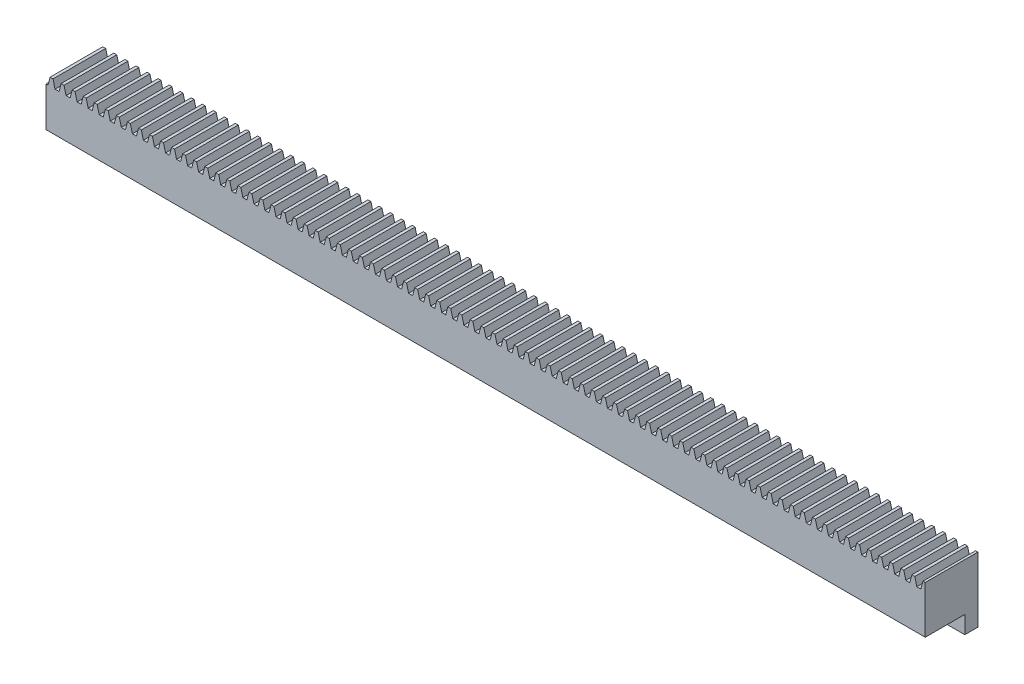
SolidWorks part; units mm, degrees
extrude "Blank" add sketch "BlankSke" against normal blind 12
sketch "BlankSke" plane through (0, 0, 0) normal (0, 0, 1) x (1, 0, 0)
  line L1 (0, 0) -> (200, 0)
  line L2 (0, 0) -> (0, 10.8)
  line L3 (0, 10.8) -> (200, 10.8)
  line L4 (200, 0) -> (200, 10.8)
  dimension "Length" = 200
  dimension "Blank_height" = 10.8
ref_plane "Plane1" through (0, 0, 0) normal (0, 0, 1) x (1, 0, 0)
ref_plane "Plane2" through (0, 0, 0) normal (0, 1, 0) x (1, 0, 0)
ref_plane "Plane3" through (0, 0, 0) normal (1, 0, 0) x (0, 0, -1)
other "Configuration Table"
sketch "HoldingSke" plane through (0, 0, 0) normal (0, 1, 0) x (1, 0, 0)
  line L0 (0, 0) -> (0.174, 1.2378)
  line L1 (-15, 0) -> (100, 0) construction
  line L2 (0, 0) -> (-2.1039, 2.3779)
  line L3 (0, 0) -> (-11.863, 4.5341)
  line L4 (0, 0) -> (1.351, 8.5297)
  line L5 (0, 0) -> (-23.7986, -8.8762)
  line L6 (0, 0) -> (-10.5278, -7.1032)
  line L9 (-67.7845, 28.3722) -> (125.845, 78.4482)
  line L10 (-76.2, 3.1779) -> (-66.2, 3.1779)
  line L11 (0, 0) -> (-12, 0)
  line L12 (-76.2, 101.6) -> (-76.17, 101.6)
  line L13 (24.9733, 27.94) -> (52.9518, 28.4284)
  line L14 (24.9733, 27.94) -> (24.9743, 27.94)
  line L15 (24.9733, 27.94) -> (100.4006, 29.5858)
  circle A0 centre (0, 0) radius 19.05
  circle A1 centre (0, 0) radius 5
  circle A2 centre (0, 0) radius 12.7
  dimension "MPH" = 10
  dimension "Diameter" = 38.1
  dimension "Num_teeth" = 81
  dimension "Pitch" = 1.25
  dimension "Show_teeth" = 998
  dimension "Thickness" = 12.7
  dimension "Ap" = 14.5
  dimension "Pitch_height" = 10
  dimension "Width" = 12
  dimension "Backlash" = 0.03
  dimension "Addendum_fac" = 1
  dimension "Dedendum_fac" = 1.25
  dimension "Clearance_fac" = 0.25
  dimension "Dedendum_add" = 0.001
  dimension "Length" = 200
  dimension "Module" = 0.8
sketch "TooCutSkeIll" plane through (0, 0, 0) normal (0, 0, 1) x (1, 0, 0)
  line L0 (-0.919, 10.776) -> (-0.4987, 9.1507)
  line L1 (-0.3041, 9) -> (0.3041, 9)
  line L2 (0.4987, 9.1507) -> (0.919, 10.776)
  line L3 (200, 10.8) -> (0, 10.8) construction
  line L4 (0, 0) -> (0, 64.897) construction
  line L5 (-13.208, 10) -> (12.954, 10) construction
  line L6 (0, 0) -> (200, 0) construction
  line L7 (0.7183, 10) -> (0.7183, 48.7463) construction
  line L8 (-0.7183, 10) -> (-0.7183, 48.7463) construction
  line L9 (0.95, 10.8) -> (0.95, 10.8254)
  line L10 (-0.95, 10.8) -> (-0.95, 10.8254)
  line L11 (-0.95, 10.8254) -> (0.95, 10.8254)
  arc A0 (0.3041, 9) -> (0.4987, 9.1507) centre (0.3041, 9.201) ccw
  arc A1 (-0.4987, 9.1507) -> (-0.3041, 9) centre (-0.3041, 9.201) ccw
  arc A2 (0.95, 10.8) -> (0.919, 10.776) centre (0.95, 10.768) ccw
  arc A3 (-0.919, 10.776) -> (-0.95, 10.8) centre (-0.95, 10.768) ccw
  dimension "Pitch_height" = 10
  dimension "Addendum_plus" = 0.8254
  dimension "Pressure_angle" = 14.5
  dimension "Gap_width" = 1.4366
  dimension "Dedendum" = 1
extrude "ToothCutIll" [suppressed] cut sketch "TooCutSkeIll" against normal through all
sketch "TooCutSkeSim" plane through (0, 0, 0) normal (0, 0, 1) x (1, 0, 0)
  line L0 (0.4597, 9) -> (-0.4597, 9)
  line L1 (0.9318, 10.8254) -> (0.4597, 9)
  line L2 (0, 17.4625) -> (0, 53.467) construction
  line L3 (0.9318, 10.8254) -> (-0.9318, 10.8254)
  line L6 (-0.9318, 10.8254) -> (-0.4597, 9)
  line L9 (-0.7183, 10) -> (0.7183, 10) construction
  line L10 (0, 0) -> (200, 0) construction
  line L11 (0.7183, 10) -> (0.7183, 53.467) construction
  line L12 (-0.7183, 10) -> (-0.7183, 53.467) construction
  dimension "Pitch_height" = 10
  dimension "Addendum_plus" = 0.8254
  dimension "Pressure_angle" = 14.5
  dimension "Gap_width" = 1.4366
  dimension "Dedendum" = 1
extrude "ToothCutSim" cut sketch "TooCutSkeSim" against normal through all
pattern_linear "TeethCuts" count 80 spacing 2.5133 along (1, 0, 0) of "ToothCutIll", "ToothCutSim"
sketch "Sketch1" plane through (0, 0, 0) normal (0, -1, 0) x (1, 0, 0)
  line L0 (0, -12) -> (0, 0) construction
  line L1 (200, -12) -> (0, -12)
  line L2 (200, -12) -> (200, -9)
  line L3 (200, -9) -> (0, -9)
  line L4 (0, -12) -> (0, -9)
  dimension "D1" = 3
extrude "Boss-Extrude1" add sketch "Sketch1" along normal blind 4
equation "' \"Module@HoldingSke\" = 6.35"
equation "' \"Num_teeth@HoldingSke\" = 12"
equation "' \"Ap@HoldingSke\" =  20"
equation "' \"Ap@HoldingSke\" = 20"
equation "' \"Width@HoldingSke\" = 0.25 * 25.4"
equation "' \"Show_teeth@HoldingSke\" = 500"
equation "' \"Backlash@HoldingSke\" = 0.009 * 25.4"
equation "' \"Addendum_fac@HoldingSke\" = 1.0"
equation "' \"Dedendum_fac@HoldingSke\" = 1.25"
equation "' \"Dedendum_add@HoldingSke\" = 0.00005 * 25.4"
equation "' \"Clearance_fac@HoldingSke\" = 0.25"
equation "' \"Pitch_height@HoldingSke\" = 1 * 25.4"
equation "' \"Length@HoldingSke\" = 4.71 * 25.4"
equation "\"Pitch@HoldingSke\" = 1 / \"Module@HoldingSke\""
equation "\"MPH@HoldingSke\" = \"Dedendum_fac@HoldingSke\" / \"Pitch@HoldingSke\" + 2 * \"Dedendum_add@HoldingSke\" + 0.002 * 25.4"
equation "\"MPH@HoldingSke\" = ((sgn( \"MPH@HoldingSke\" - \"Pitch_height@HoldingSke\")+1)*( \"MPH@HoldingSke\" - \"Pitch_height@HoldingSke\"))/2 + \"Pitch_height@HoldingSke\""
equation "\"Blank_height@BlankSke\" = \"Pitch_height@HoldingSke\" + \"Addendum_fac@HoldingSke\"  / \"Pitch@HoldingSke\" "
equation "\"Length@BlankSke\" =  \"Length@HoldingSke\""
equation "\"Face_width@Blank\" = \"Width@HoldingSke\""
equation "\"Pressure_angle@TooCutSkeIll\" = \"Ap@HoldingSke\""
equation "\"Addendum_plus@TooCutSkeIll\" =  \"Addendum_fac@HoldingSke\"  / \"Pitch@HoldingSke\" + 0.001 *25.4"
equation "\"Dedendum@TooCutSkeIll\" = \"Dedendum_fac@HoldingSke\"  / \"Pitch@HoldingSke\""
equation "\"Pitch_height@TooCutSkeIll\" =  \"MPH@HoldingSke\""
equation "\"Gap_width@TooCutSkeIll\" = 3.14159265 / 2 / \"Pitch@HoldingSke\" + 6 * \"Backlash@HoldingSke\""
equation "\"Pressure_angle@TooCutSkeSim\" = \"Ap@HoldingSke\""
equation "\"Addendum_plus@TooCutSkeSim\" =  \"Addendum_fac@HoldingSke\"  / \"Pitch@HoldingSke\" + 0.001 * 25.4"
equation "\"Dedendum@TooCutSkeSim\" = \"Dedendum_fac@HoldingSke\"  / \"Pitch@HoldingSke\""
equation "\"Pitch_height@TooCutSkeSim\" =  \"MPH@HoldingSke\""
equation "\"Gap_width@TooCutSkeSim\" = 3.14159265 / 2 / \"Pitch@HoldingSke\" + 6 * \"Backlash@HoldingSke\""
equation "\"Root_fillet@TooCutSkeIll\" = \"Clearance_fac@HoldingSke\" / \"Pitch@HoldingSke\" + \"Dedendum_add@HoldingSke\""
equation "\"Break_rad@TooCutSkeIll\" = 0.02 / \"Pitch@HoldingSke\" * 2"
equation "\"Linear_pitch@TeethCuts\" = 3.14159265 / \"Pitch@HoldingSke\""
equation "\"Num_teeth@HoldingSke\" = int( ( \"Length@HoldingSke\" + 0 ) / (3.14159265 / \"Pitch@HoldingSke\")) + 0.9999  + 1"
equation " \"Num_teeth@TeethCuts\" = int( \"Show_teeth@HoldingSke\" ) + 1"
equation " \"Num_teeth@TeethCuts\" = ((sgn( \"Num_teeth@TeethCuts\" - \"Num_teeth@HoldingSke\" )-1)*( \"Num_teeth@TeethCuts\" - \"Num_teeth@HoldingSke\" ))/-2+ \"Num_teeth@HoldingSke\""
equation " \"Num_teeth@TeethCuts\" = ((sgn( \"Num_teeth@TeethCuts\" - 2.0)+1)*( \"Num_teeth@TeethCuts\" - 2.0))/2 +2.0"
